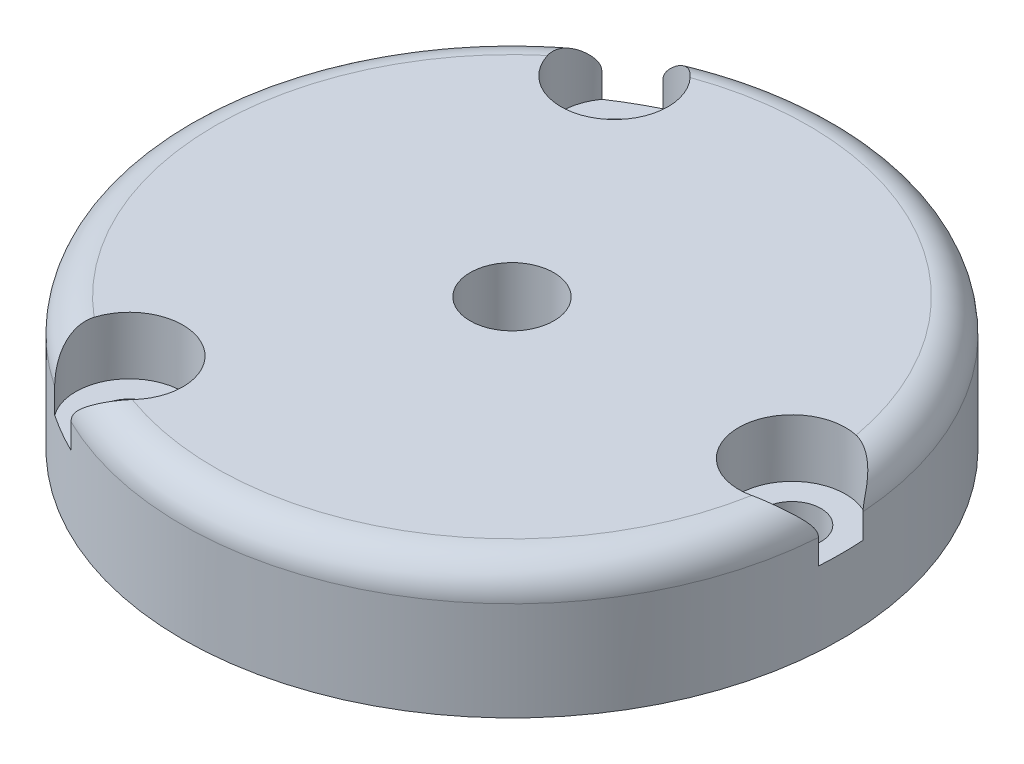
SolidWorks part; units mm, degrees
ref_plane "Front Plane" through (0, 0, 0) normal (0, 0, 1) x (1, 0, 0)
ref_plane "Top Plane" through (0, 0, 0) normal (0, 1, 0) x (1, 0, 0)
ref_plane "Right Plane" through (0, 0, 0) normal (1, 0, 0) x (0, 0, -1)
sketch "Sketch1" plane through (0, 0, 0) normal (0, 1, 0) x (1, 0, 0)
  circle A0 centre (0, 0) radius 20
  circle A1 centre (0, 0) radius 17 construction
  circle A3 centre (17, 0) radius 1.75
  circle A4 centre (-8.5, -14.7224) radius 1.75
  circle A5 centre (-8.5, 14.7224) radius 1.75
  dimension "D1" = 40
  dimension "D2" = 34
  dimension "D3" = 3.5
  dimension "D4" = 3
extrude "Boss-Extrude1" add sketch "Sketch1" along normal blind 8
sketch "Sketch2" plane through (0, 8, 0) normal (0, 1, 0) x (1, 0, 0)
  circle A0 centre (17, 0) radius 3.25
  circle A1 centre (-8.5, -14.7224) radius 3.25
  circle A2 centre (-8.5, 14.7224) radius 3.25
  circle A3 centre (0, 0) radius 17 construction
  dimension "D1" = 3
extrude "Cut-Extrude1" cut sketch "Sketch2" against normal blind 3.5
sketch "Sketch3" plane through (0, 8, 0) normal (0, 1, 0) x (1, 0, 0)
  circle A0 centre (0, 0) radius 2.54
extrude "Cut-Extrude2" cut sketch "Sketch3" against normal through all
sketch "Sketch4" plane through (0, 8, 0) normal (0, 1, 0) x (1, 0, 0)
  circle A0 centre (0, 0) radius 4.7625
extrude "Cut-Extrude3" [suppressed] cut sketch "Sketch4" against normal blind 3.302
fillet "Fillet1" radius 2 3 edges at (10, 8, -17.3205) (-20, 8, 0) (10, 8, 17.3205)
fillet "Fillet2" [suppressed] radius 1
sketch "Sketch5" plane through (0, 0, 0) normal (0, -1, 0) x (1, 0, 0)
  circle A3 centre (0, 0) radius 17.125 construction
  circle A4 centre (0, 17.125) radius 2.5
extrude "Cut-Extrude6" [suppressed] cut sketch "Sketch5" against normal blind 2.125 contours A4
